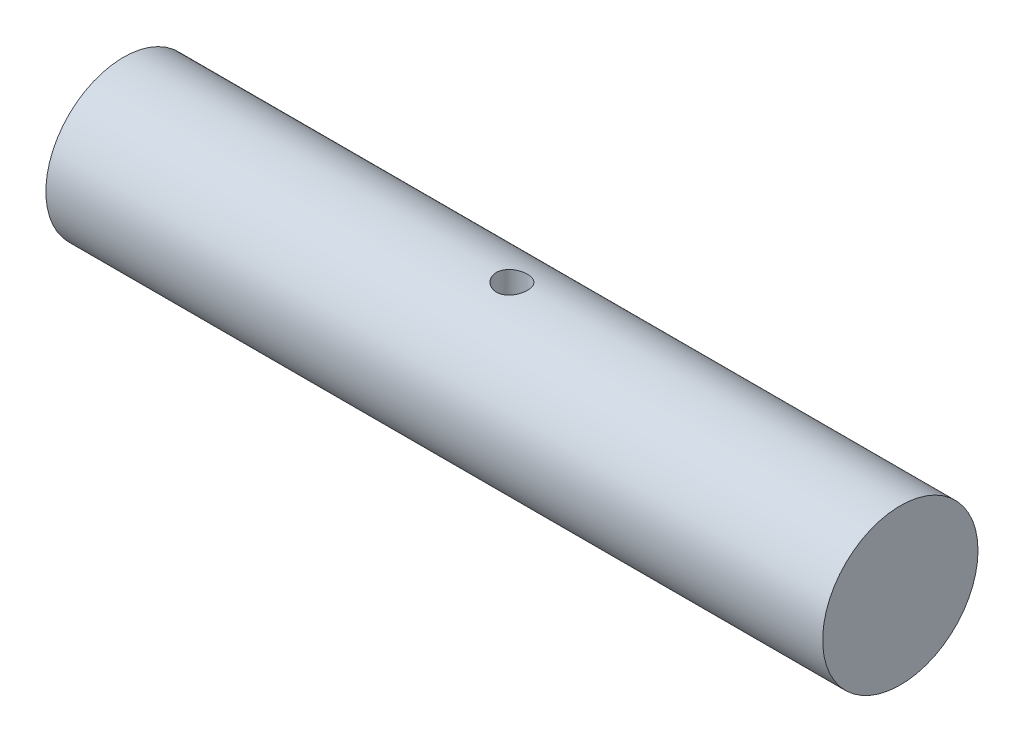
SolidWorks part; units mm, degrees
ref_plane "Front Plane" through (0, 0, 0) normal (0, 0, 1) x (1, 0, 0)
ref_plane "Top Plane" through (0, 0, 0) normal (0, 1, 0) x (1, 0, 0)
ref_plane "Right Plane" through (0, 0, 0) normal (1, 0, 0) x (0, 0, -1)
sketch "Sketch1" plane through (0, 0, 0) normal (1, 0, 0) x (0, 0, -1)
  circle A0 centre (0, 0) radius 25
  dimension "D1" = 50
extrude "Boss-Extrude1" add sketch "Sketch1" along normal mid plane 250
sketch "Sketch2" plane through (0, 0, 0) normal (0, 1, 0) x (1, 0, 0)
  circle A0 centre (0, 0) radius 5
  dimension "D1" = 10
extrude "Cut-Extrude1" cut sketch "Sketch2" against normal through all both and the other way through all
